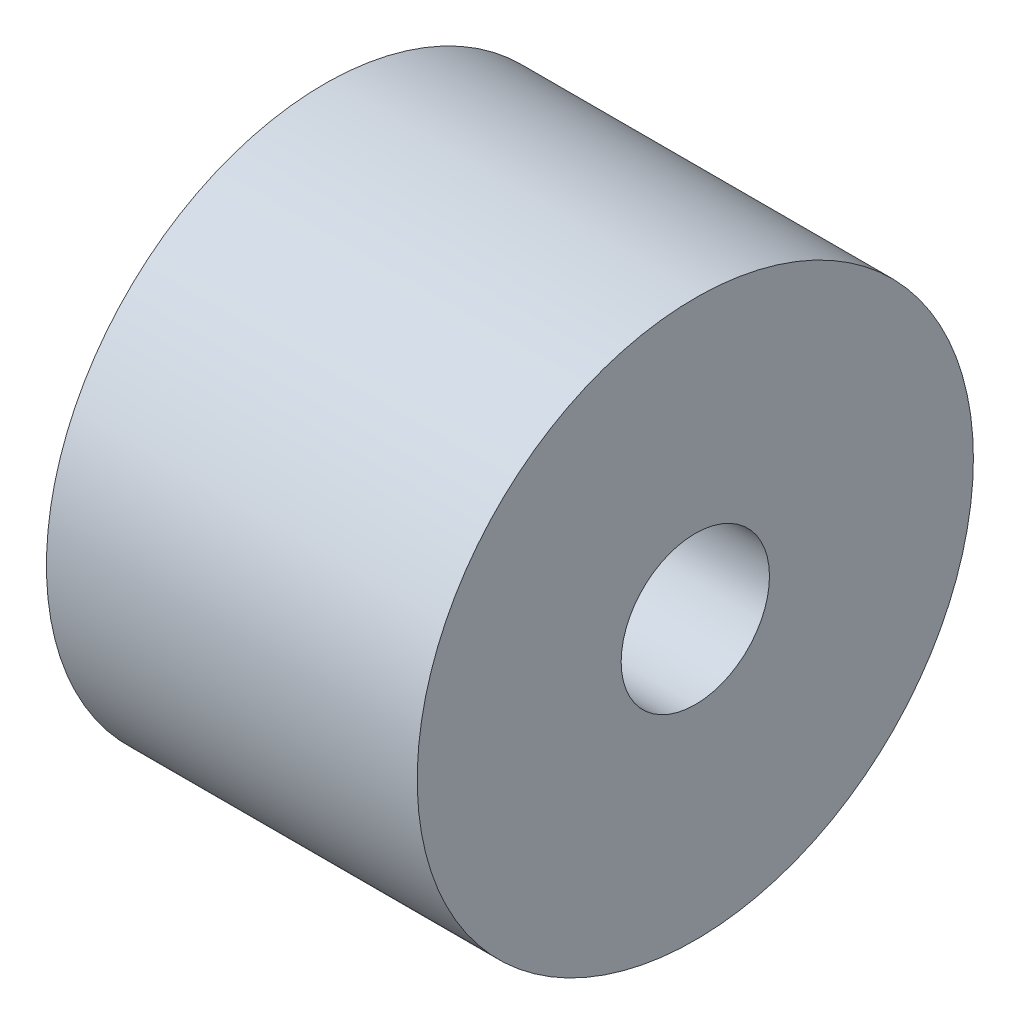
SolidWorks part; units mm, degrees
ref_plane "Plan de face" through (0, 0, 0) normal (0, 0, 1) x (1, 0, 0)
ref_plane "Plan de dessus" through (0, 0, 0) normal (0, 1, 0) x (1, 0, 0)
ref_plane "Plan de droite" through (0, 0, 0) normal (1, 0, 0) x (0, 0, -1)
sketch "Esquisse1" plane through (0, 0, 0) normal (1, 0, 0) x (0, 0, -1)
  circle A0 centre (-27.1526, -173.602) radius 15
  circle A1 centre (-27.1526, -173.602) radius 4
  dimension "D1" = 30
  dimension "D2" = 8
extrude "Boss.-Extru.1" add sketch "Esquisse1" along normal blind 20
sketch "Esquisse2" plane through (0, 0, 0) normal (-1, 0, 0) x (0, 0, 1)
  line L1 (21.8235, -178.8874) -> (29.0653, -180.8598)
  line L2 (29.0653, -180.8598) -> (34.3943, -175.5744)
  line L3 (34.3943, -175.5744) -> (32.4816, -168.3167)
  line L4 (32.4816, -168.3167) -> (25.2398, -166.3443)
  line L5 (25.2398, -166.3443) -> (19.9108, -171.6296)
  line L6 (19.9108, -171.6296) -> (21.8235, -178.8874)
  circle A0 centre (27.1526, -173.602) radius 6.5 construction
extrude "Enlèv. mat.-Extru.1" cut sketch "Esquisse2" against normal blind 8
